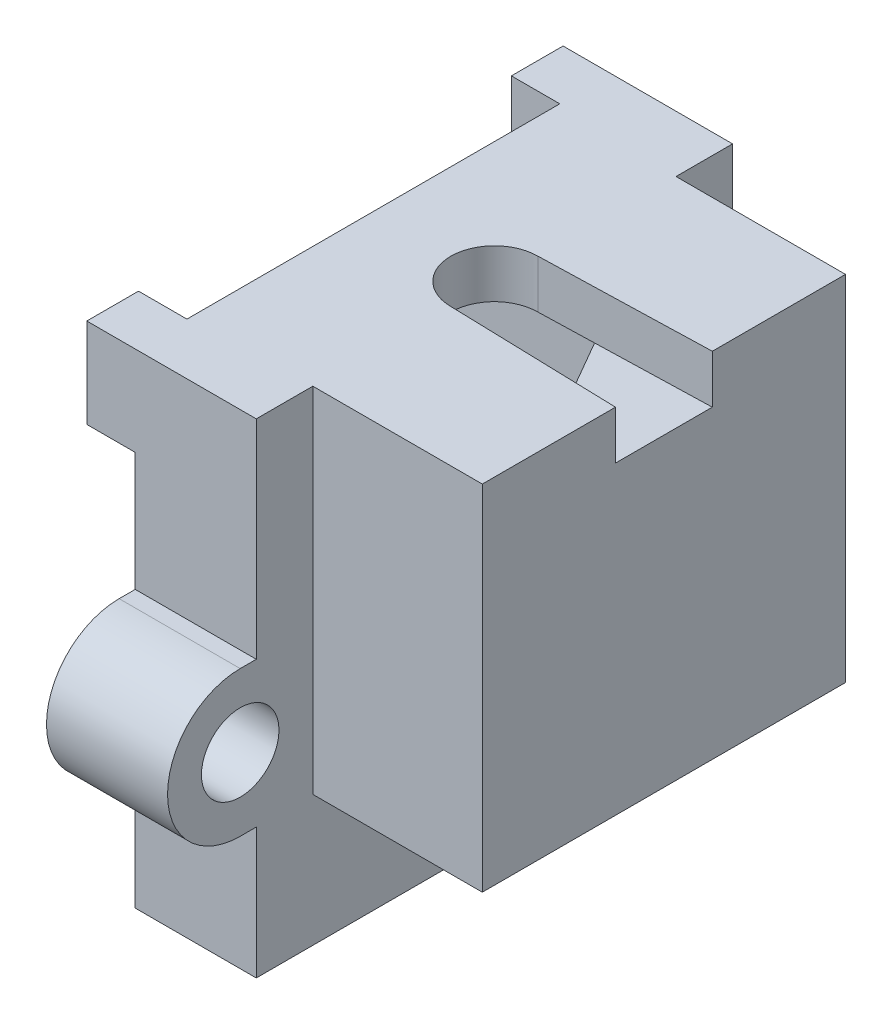
SolidWorks part; units mm, degrees
ref_plane "Front Plane" through (0, 0, 0) normal (0, 0, 1) x (1, 0, 0)
ref_plane "Top Plane" through (0, 0, 0) normal (0, 1, 0) x (1, 0, 0)
ref_plane "Right Plane" through (0, 0, 0) normal (1, 0, 0) x (0, 0, -1)
sketch "Sketch1" plane through (0, 0, 0) normal (0, 1, 0) x (1, 0, 0)
  line L1 (-6, -7.5) -> (6, -7.5)
  line L2 (-6, -7.5) -> (-6, 7.5)
  line L3 (-6, 7.5) -> (6, 7.5)
  line L4 (6, -7.5) -> (6, 7.5)
  line L5 (-6, -7.5) -> (6, 7.5) construction
  line L6 (-6, 7.5) -> (6, -7.5) construction
  point P0 (0, 0)
extrude "Boss-Extrude1" add sketch "Sketch1" along normal blind 20
sketch "Sketch2" plane through (-6, 0, 0) normal (-1, 0, 0) x (0, 0, 1)
  line L1 (-7.5, 20) -> (-7.5, 0) construction
  line L2 (7.5, 20) -> (7.5, 0) construction
  line L3 (10.5, 11.4) -> (7.5, 11.4)
  line L4 (7.5, 11.4) -> (7.5, 5.4)
  line L5 (7.5, 5.4) -> (10.5, 5.4)
  line L6 (-10.5, 11.4) -> (-7.5, 11.4)
  line L7 (-7.5, 11.4) -> (-7.5, 5.4)
  line L8 (-7.5, 5.4) -> (-10.5, 5.4)
  arc A0 (-10.5, 11.4) -> (-10.5, 5.4) centre (-10.5, 8.4) ccw
  arc A1 (10.5, 5.4) -> (10.5, 11.4) centre (10.5, 8.4) ccw
  circle A2 centre (10.5, 8.4) radius 1.6
  circle A3 centre (-10.5, 8.4) radius 1.6
extrude "Boss-Extrude2" add sketch "Sketch2" against normal blind 5
sketch "Sketch3" plane through (0, 20, 0) normal (0, 1, 0) x (1, 0, 0)
  line L0 (-6, 0) -> (6, 0) construction
  line L1 (-6, 7.5) -> (-6, -7.5) construction
  line L2 (6, -7.5) -> (6, 7.5) construction
  line L3 (-1, 48) -> (-1, 0) construction
  line L4 (-1, 32.6) -> (-1, 63.4) construction
  circle A0 centre (-1, 0) radius 1.6
extrude "Cut-Extrude1" cut sketch "Sketch3" against normal blind 10
ref_plane "Plane1" through (0, 18, 0) normal (0, 1, 0) x (1, 0, 0)
sketch "Sketch4" plane through (0, 18, 0) normal (0, 1, 0) x (1, 0, 0)
  line L0 (-2.6743, 2.9) -> (-6, 2.9)
  line L1 (2.3486, 0) -> (0.6743, 2.9)
  line L2 (0.6743, 2.9) -> (-2.6743, 2.9)
  line L3 (-2.6743, 2.9) -> (-4.3486, 0) construction
  line L4 (-4.3486, 0) -> (-2.6743, -2.9) construction
  line L5 (-2.6743, -2.9) -> (0.6743, -2.9)
  line L6 (0.6743, -2.9) -> (2.3486, 0)
  line L7 (-6, 7.5) -> (-6, -7.5) construction
  line L8 (-6, 2.9) -> (-6, -2.9)
  line L9 (-6, -2.9) -> (-2.6743, -2.9)
  circle A0 centre (-1, 0) radius 2.9 construction
extrude "Cut-Extrude2" cut sketch "Sketch4" against normal blind 3
sketch "Sketch5" plane through (0, 18, 0) normal (0, 1, 0) x (1, 0, 0)
  line L0 (-1, 1.8) -> (6, 2)
  line L1 (6, -7.5) -> (6, 7.5) construction
  line L2 (6, 2) -> (6, 0)
  line L3 (6, 0) -> (6, -2)
  line L4 (6, -2) -> (-1, -1.8)
  line L5 (-1, 0) -> (6, 0) construction
  arc A1 (-1, 1.8) -> (-1, -1.8) centre (-1, 0) ccw
extrude "Cut-Extrude3" cut sketch "Sketch5" along normal up to vertex (2 mm away)
sketch "Sketch6" plane through (0, 20, 0) normal (0, 1, 0) x (1, 0, 0)
  line L8 (-6, 7.7) -> (-6, 7.5)
  line L9 (-8, 7.7) -> (-6, 7.7)
  line L10 (-8, 7.7) -> (-6, 7.7)
  line L11 (-8, 7.7) -> (-8, 9.8361)
  line L13 (-8, 9.8361) -> (-1, 9.8361)
  line L14 (-1, 9.8361) -> (-1, 7.5)
  line L15 (6, 7.5) -> (-6, 7.5) construction
  line L16 (-1, 7.5) -> (-6, 7.5)
  line L17 (-8, 0) -> (6, 0) construction
  line L18 (-8, 7.5) -> (-8, -7.5) construction
  line L19 (6, -2) -> (6, 2) construction
  line L20 (-1, -7.5) -> (-6, -7.5)
  line L21 (-1, -9.8361) -> (-1, -7.5)
  line L22 (-8, -9.8361) -> (-1, -9.8361)
  line L23 (-8, -7.7) -> (-8, -9.8361)
  line L24 (-8, -7.7) -> (-6, -7.7)
  line L25 (-6, -7.7) -> (-6, -7.5)
  line L33 (-1, 7.5) -> (-1, 10.5) construction
  dimension "D1" = 0.2
extrude "Boss-Extrude4" add sketch "Sketch6" against normal blind 3.7
sketch "Sketch8" plane through (-1, 0, 0) normal (1, 0, 0) x (0, 0, -1)
  line L0 (-10.5, 11.4) -> (-7.5, 11.4) construction
  line L1 (-7.5, 20) -> (-9.8361, 20)
  line L2 (-7.5, 20) -> (-7.5, 11.4)
  line L3 (-7.5, 11.4) -> (-9.8361, 11.4)
  line L4 (-9.8361, 20) -> (-9.8361, 11.4)
  line L6 (9.8361, 20) -> (7.5, 20)
  line L7 (9.8361, 20) -> (9.8361, 11.4)
  line L8 (9.8361, 11.4) -> (7.5, 11.4)
  line L9 (7.5, 20) -> (7.5, 11.4)
extrude "Boss-Extrude5" add sketch "Sketch8" against normal up to vertex
sketch "Sketch10" plane through (6, 0, 0) normal (1, 0, 0) x (0, 0, -1)
  line L1 (-7.5, 0) -> (7.5, 0)
  line L2 (-7.5, 0) -> (-7.5, 5.4)
  line L3 (-7.5, 5.4) -> (7.5, 5.4)
  line L4 (7.5, 0) -> (7.5, 5.4)
  line L5 (10.5, 5.4) -> (7.5, 5.4) construction
extrude "Cut-Extrude5" cut sketch "Sketch10" against normal up to vertex (7 mm away)
sketch "Sketch13" plane through (-1, 0, 0) normal (1, 0, 0) x (0, 0, -1)
  line L0 (10.5, 5.4) -> (7.5, 5.4) construction
  line L1 (9.8361, 5.4) -> (-9.8361, 5.4)
  line L2 (9.8361, 5.4) -> (9.8361, 0)
  line L3 (9.8361, 0) -> (-9.8361, 0)
  line L4 (-9.8361, 5.4) -> (-9.8361, 0)
extrude "Boss-Extrude8" add sketch "Sketch13" against normal up to vertex
